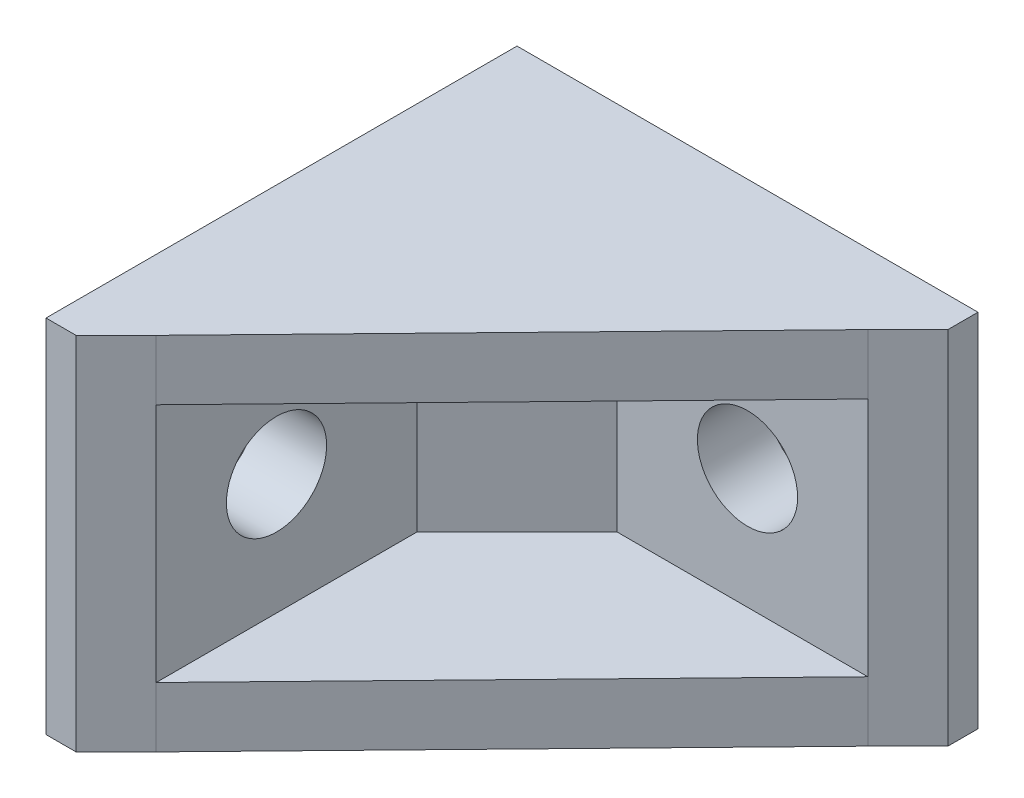
SolidWorks part; units mm, degrees
ref_plane "Plan de face" through (0, 0, 0) normal (0, 0, 1) x (1, 0, 0)
ref_plane "Plan de dessus" through (0, 0, 0) normal (0, 1, 0) x (1, 0, 0)
ref_plane "Plan de droite" through (0, 0, 0) normal (1, 0, 0) x (0, 0, -1)
sketch "Esquisse1" plane through (0, 0, 0) normal (0, 0, 1) x (1, 0, 0)
  line L1 (-10.6639, 14.76) -> (12.3361, 14.76)
  line L2 (-10.6639, 14.76) -> (-10.6639, -3.24)
  line L3 (-10.6639, -3.24) -> (12.3361, -3.24)
  line L4 (12.3361, 14.76) -> (12.3361, -3.24)
  dimension "D1" = 18
  dimension "D2" = 23
extrude "Boss.-Extru.1" add sketch "Esquisse1" along normal blind 3.5
sketch "Esquisse2" plane through (0, 0, 3.5) normal (0, 0, 1) x (1, 0, 0)
  line L0 (12.3361, 14.76) -> (-10.6639, 14.76) construction
  line L1 (-10.6639, -3.24) -> (-7.1639, -3.24)
  line L2 (-10.6639, -3.24) -> (-10.6639, 14.76)
  line L3 (-10.6639, 14.76) -> (-7.1639, 14.76)
  line L4 (-7.1639, -3.24) -> (-7.1639, 14.76)
  dimension "D1" = 3.5
extrude "Boss.-Extru.2" add sketch "Esquisse2" along normal blind 20
sketch "Esquisse3" plane through (0, 0, 3.5) normal (0, 0, 1) x (1, 0, 0)
  line L0 (12.3361, 5.76) -> (-7.1639, 5.76) construction
  line L1 (12.3361, -3.24) -> (12.3361, 14.76) construction
  line L2 (-7.1639, -3.24) -> (-7.1639, 14.76) construction
  circle A0 centre (4.3361, 5.76) radius 2.5
  dimension "D1" = 5
  dimension "D2" = 8
extrude "Enlèv. mat.-Extru.1" cut sketch "Esquisse3" against normal blind 20
sketch "Esquisse4" plane through (-7.1639, 0, 0) normal (1, 0, 0) x (0, 0, -1)
  line L0 (-23.5, 5.76) -> (-3.5, 5.76) construction
  line L1 (-23.5, -3.24) -> (-23.5, 14.76) construction
  line L2 (-3.5, -3.24) -> (-3.5, 14.76) construction
  circle A0 centre (-15.5, 5.76) radius 2.5
  dimension "D1" = 5
  dimension "D2" = 8
extrude "Enlèv. mat.-Extru.2" cut sketch "Esquisse4" against normal blind 20
chamfer "Chanfrein1" distance 5 angle 45 1 edges at (-7.1639, 5.76, 3.5)
chamfer "Chanfrein2" distance 2 angle 45 2 edges at (-7.1639, 5.76, 23.5) (12.3361, 5.76, 3.5)
sketch "Esquisse5" plane through (0, 14.76, 0) normal (0, 1, 0) x (1, 0, 0)
  line L0 (10.3361, -3.5) -> (-7.1639, -21.5)
  line L1 (-7.1639, -21.5) -> (-7.1639, -8.5)
  line L2 (-7.1639, -8.5) -> (-2.1639, -3.5)
  line L3 (-2.1639, -3.5) -> (10.3361, -3.5)
extrude "Boss.-Extru.3" add sketch "Esquisse5" against normal blind 3
sketch "Esquisse6" plane through (0, -3.24, 0) normal (0, -1, 0) x (-1, 0, 0)
  line L0 (7.1639, -21.5) -> (-10.3361, -3.5)
  line L1 (-10.3361, -3.5) -> (2.1639, -3.5)
  line L2 (2.1639, -3.5) -> (7.1639, -8.5)
  line L3 (7.1639, -8.5) -> (7.1639, -21.5)
extrude "Boss.-Extru.4" add sketch "Esquisse6" against normal blind 3
